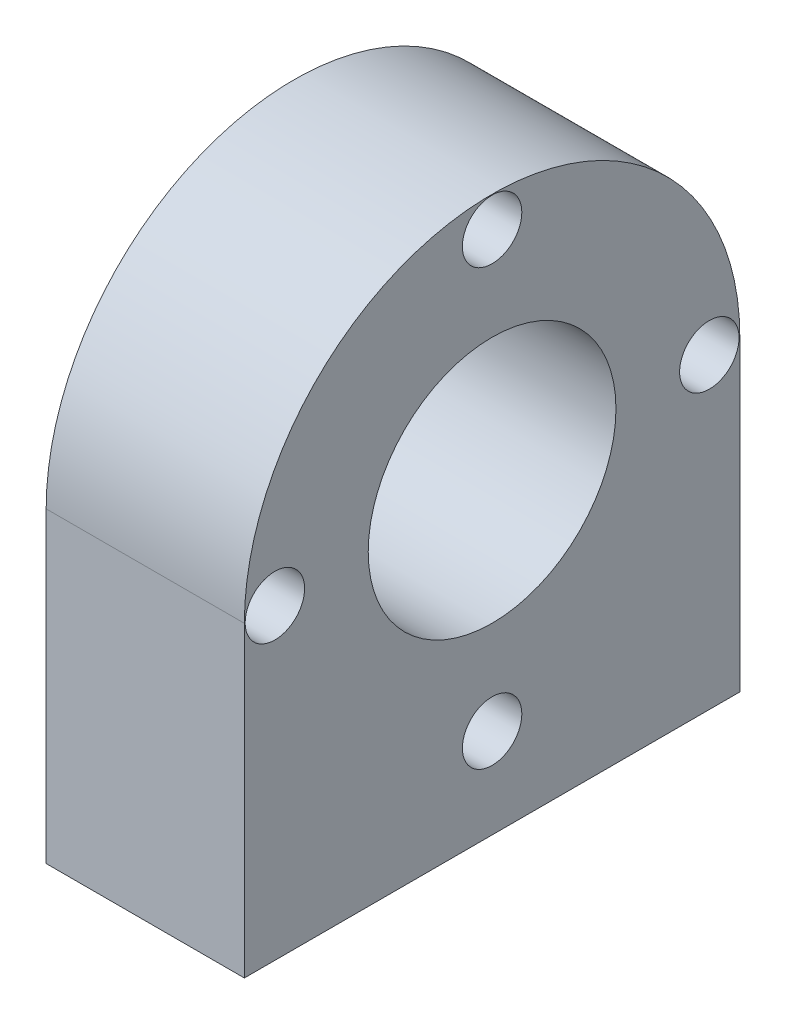
SolidWorks part; units mm, degrees
ref_plane "Ebene vorne" through (0, 0, 0) normal (0, 0, 1) x (1, 0, 0)
ref_plane "Ebene oben" through (0, 0, 0) normal (0, 1, 0) x (1, 0, 0)
ref_plane "Ebene rechts" through (0, 0, 0) normal (1, 0, 0) x (0, 0, -1)
sketch "Skizze1" plane through (0, 0, 0) normal (0, 1, 0) x (1, 0, 0)
  line L1 (-10, -25) -> (10, -25)
  line L2 (-10, -25) -> (-10, 25)
  line L3 (-10, 25) -> (10, 25)
  line L4 (10, -25) -> (10, 25)
  line L5 (-10, -25) -> (10, 25) construction
  line L6 (-10, 25) -> (10, -25) construction
  point P0 (0, 0)
  dimension "D1" = 20
  dimension "D2" = 50
extrude "Aufsatz-Linear austragen1" add sketch "Skizze1" along normal blind 56
sketch "Skizze2" plane through (-10, 0, 0) normal (-1, 0, 0) x (0, 0, 1)
  line L0 (-25, 56) -> (25, 56) construction
  line L1 (-25, 56) -> (-25, 0) construction
  line L2 (25, 56) -> (25, 0) construction
  line L3 (-25, 31) -> (-25, 56)
  line L4 (-25, 56) -> (25, 56)
  line L5 (25, 56) -> (25, 31)
  circle A0 centre (0, 31) radius 25
  circle A1 centre (0, 31) radius 12.5
  circle A2 centre (0, 31) radius 17.5
  point P15 (0, 31)
  line M7 (25, 0) -> (25, 56)
  line M8 (25, 56) -> (-25, 56)
  line M9 (-25, 56) -> (-25, 0)
  dimension "D1" = 25
  dimension "D2" = 35
extrude "Schnitt-Linear austragen1" cut sketch "Skizze2" against normal through all contours A0 L4 M9 | A0 M7 M8 | A1
sketch "Skizze3" plane through (0, 0, 0) normal (0, -1, 0) x (1, 0, 0)
  line L0 (0, 25) -> (0, -25) construction
  line L1 (-10, 25) -> (10, 25) construction
  line L2 (10, -25) -> (-10, -25) construction
  line L4 (0, 0) -> (3.2712, 0) construction
  circle A0 centre (0, 19) radius 1.65
  circle A1 centre (0, 9) radius 1.65
  circle A2 centre (0, -9) radius 1.65
  circle A3 centre (0, -19) radius 1.65
  dimension "D1" = 3.3
  dimension "D2" = 3.3
  dimension "D3" = 6
  dimension "D4" = 10
extrude "Schnitt-Linear austragen2" cut sketch "Skizze3" against normal blind 15 contours A0 | A1 | A2 | A3
sketch "Skizze4" plane through (-10, 0, 0) normal (-1, 0, 0) x (0, 0, 1)
  line L0 (0, 31) -> (0, 52.9203) construction
  line L1 (-15.5, 15.5) -> (15.5, 15.5)
  line L2 (-15.5, 15.5) -> (-15.5, 46.5)
  line L3 (-15.5, 46.5) -> (15.5, 46.5)
  line L4 (15.5, 15.5) -> (15.5, 46.5)
  line L5 (-15.5, 15.5) -> (15.5, 46.5) construction
  line L6 (-15.5, 46.5) -> (15.5, 15.5) construction
  line L7 (0, 52.9203) -> (0, 31) construction
  line L8 (0, 31) -> (-21.9203, 31) construction
  circle A6 centre (-21.9203, 31) radius 1.5
  circle A8 centre (0, 52.9203) radius 1.5
  circle A9 centre (21.9203, 31) radius 1.5
  circle A10 centre (0, 9.0797) radius 1.5
  point P0 (0, 31)
  point P21 (0, 31)
  point P22 (0, 31)
  dimension "D1" = 31
  dimension "D4" = 4
  dimension "D2" = 31
  dimension "D3" = 31
extrude "Schnitt-Linear austragen3" cut sketch "Skizze4" against normal blind 20 contours A6 | A8 | A9 | A10
sketch "Skizze5" plane through (10, 0, 0) normal (1, 0, 0) x (0, 0, -1)
  circle A1 centre (0, 31) radius 12.5
  circle A6 centre (21.9203, 31) radius 3
  circle A7 centre (0, 9.0797) radius 3
  circle A8 centre (-21.9203, 31) radius 3
  circle A9 centre (0, 52.9203) radius 3
  point P14 (0.1352, 29.7778)
  point P16 (0, 31)
  dimension "D1" = 4
extrude "Schnitt-Linear austragen4" cut sketch "Skizze5" against normal offset from surface 8 and the other way through all up to face at (-10, 31, -20.4203)
